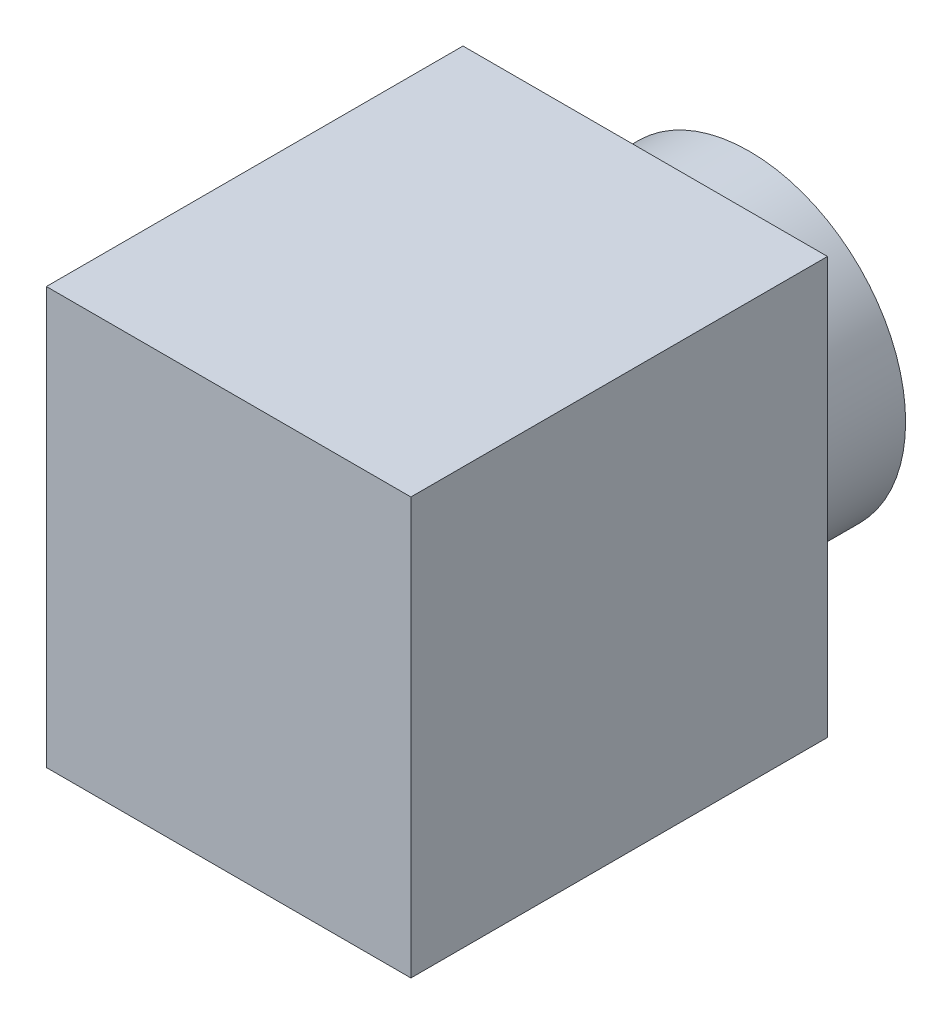
SolidWorks part; units mm, degrees
ref_plane "Alzado" through (0, 0, 0) normal (0, 0, 1) x (1, 0, 0)
ref_plane "Planta" through (0, 0, 0) normal (0, 1, 0) x (1, 0, 0)
ref_plane "Vista lateral" through (0, 0, 0) normal (1, 0, 0) x (0, 0, -1)
sketch "Croquis1" plane through (0, 0, 0) normal (0, 0, 1) x (1, 0, 0)
  line L5 (0, 0) -> (70, 0)
  line L6 (0, 0) -> (0, 80)
  line L7 (0, 80) -> (70, 80)
  line L8 (70, 0) -> (70, 80)
  dimension "D1" = 80
  dimension "D2" = 70
extrude "Saliente-Extruir1" add sketch "Croquis1" along normal blind 80
sketch "Croquis2" plane through (0, 0, 0) normal (0, 0, -1) x (-1, 0, 0)
  line L2 (-70, 0) -> (-70, 80) construction
  circle A0 centre (-35, 40) radius 30
  dimension "D1" = 60
  dimension "D2" = 40
  dimension "D3" = 35
extrude "Saliente-Extruir2" add sketch "Croquis2" along normal blind 20
sketch "Croquis3" plane through (0, 0, 0) normal (-1, 0, 0) x (0, 0, 1)
  circle A0 centre (40, 40) radius 21
  dimension "D1" = 42
  dimension "D2" = 40
  dimension "D3" = 40
extrude "Cortar-Extruir1" cut sketch "Croquis3" against normal blind 15
